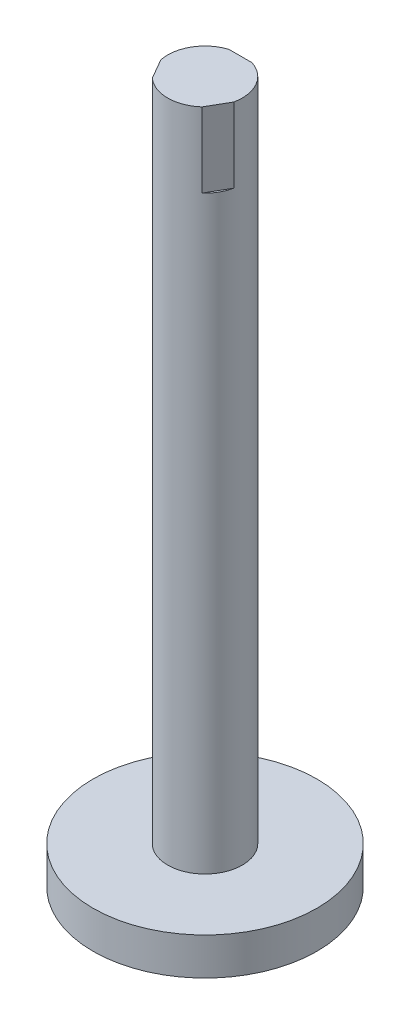
SolidWorks part; units mm, degrees
material "Plain Carbon Steel"
ref_plane "Front Plane" through (0, 0, 0) normal (0, 0, 1) x (1, 0, 0)
ref_plane "Top Plane" through (0, 0, 0) normal (0, 1, 0) x (1, 0, 0)
ref_plane "Right Plane" through (0, 0, 0) normal (1, 0, 0) x (0, 0, -1)
sketch "Sketch1" plane through (0, 0, 0) normal (0, 1, 0) x (1, 0, 0)
  circle A0 centre (0, 0) radius 15
  dimension "D1" = 30
extrude "Boss-Extrude1" add sketch "Sketch1" against normal blind 5
sketch "Sketch2" plane through (0, 0, 0) normal (0, 1, 0) x (1, 0, 0)
  circle A0 centre (0, 0) radius 5
  dimension "D1" = 10
extrude "Boss-Extrude2" add sketch "Sketch2" along normal blind 89
sketch "Sketch3" plane through (0, 0, 0) normal (0, 1, 0) x (1, 0, 0)
  circle A0 centre (-8.6603, -5) radius 2.05 construction
  circle A1 centre (8.6603, -5) radius 2.05 construction
  circle A2 centre (0, 10) radius 2.05 construction
  circle A3 centre (-8.6603, -5) radius 2.05
  circle A4 centre (8.6603, -5) radius 2.05
  circle A5 centre (0, 10) radius 2.05
sketch "Sketch7" plane through (0, 89, 0) normal (0, 1, 0) x (1, 0, 0)
  line L0 (-1.5612, 4.75) -> (1.5612, 4.75)
  circle A0 centre (0, 0) radius 5 construction
  arc A1 (1.5612, 4.75) -> (-1.5612, 4.75) centre (0, 0) ccw
  dimension "D1" = 0.25
extrude "Cut-Extrude2" cut sketch "Sketch7" against normal blind 10 contours L0 A1
pattern_circular "CirPattern1" count 3 every 120 about axis through (0, 0, 0) along (0, 1, 0) of "Cut-Extrude2"
